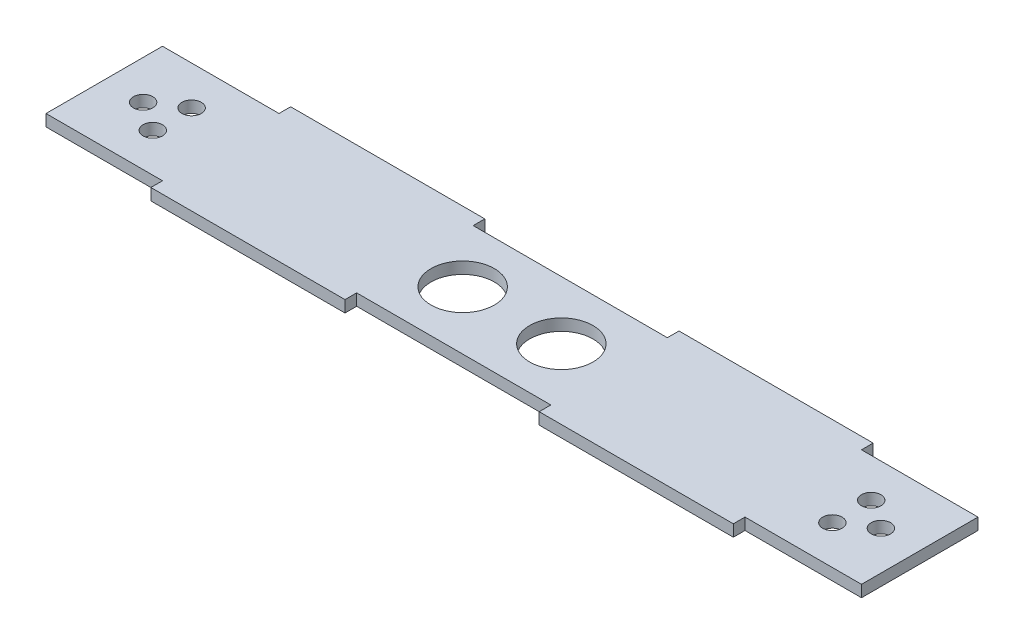
SolidWorks part; units mm, degrees
other "Markup1"
sketch "Sketch5" plane through (-105, 3, 18) normal (0, 1, 0.0048) x (1, 0, 0)
material "3mm Birch Ply Wood"
ref_plane "Front Plane" through (0, 0, 0) normal (0, 0, 1) x (1, 0, 0)
ref_plane "Top Plane" through (0, 0, 0) normal (0, 1, 0) x (1, 0, 0)
ref_plane "Right Plane" through (0, 0, 0) normal (1, 0, 0) x (0, 0, -1)
sketch "Sketch1" plane through (0, 0, 0) normal (0, 1, 0) x (1, 0, 0)
  line L1 (-105, -15) -> (105, -15)
  line L2 (-105, -15) -> (-105, 15)
  line L3 (-105, 15) -> (105, 15)
  line L4 (105, -15) -> (105, 15)
  line L5 (-105, -15) -> (105, 15) construction
  line L6 (-105, 15) -> (105, -15) construction
  point P0 (0, 0)
extrude "Boss-Extrude1" add sketch "Sketch1" along normal blind 3
sketch "Sketch2" plane through (0, 0, 0) normal (0, 1, 0) x (1, 0, 0)
  line L0 (-105, 0) -> (105, 0) construction
  line L1 (-105, 15) -> (-105, -15) construction
  line L2 (105, -15) -> (105, 15) construction
  line L3 (-105, 15) -> (-75, 15) construction
  line L4 (105, 15) -> (-105, 15) construction
  line L5 (-75, 15) -> (-75, 18)
  line L6 (-75, 18) -> (-25, 18)
  line L7 (-75, 15) -> (-25, 15)
  line L8 (-25, 15) -> (-25, 18)
  line L9 (-25, 18) -> (25, 18) construction
  line L10 (25, 18) -> (25, 15)
  line L11 (25, 15) -> (75, 15)
  line L12 (25, 18) -> (75, 18)
  line L13 (75, 18) -> (75, 15)
  line L14 (-25, -18) -> (25, -18) construction
  line L15 (-105, -15) -> (-75, -15) construction
  line L16 (75, -18) -> (75, -15)
  line L17 (25, -18) -> (75, -18)
  line L18 (25, -15) -> (75, -15)
  line L19 (25, -18) -> (25, -15)
  line L20 (-25, -15) -> (-25, -18)
  line L21 (-75, -15) -> (-25, -15)
  line L22 (-75, -18) -> (-25, -18)
  line L23 (-75, -15) -> (-75, -18)
extrude "Boss-Extrude2" add sketch "Sketch2" along normal blind 3
sketch "Sketch3" plane through (0, 3, 0) normal (0, 1, 0) x (1, 0, 0)
  line L0 (0, 15) -> (0, 0) construction
  line L1 (25, 15) -> (-25, 15) construction
  line L2 (0, 0) -> (-12.7, 0) construction
  circle A0 centre (-12.7, 0) radius 8.15
  circle A1 centre (12.7, 0) radius 8.15
extrude "Cut-Extrude1" cut sketch "Sketch3" against normal blind 10
sketch "Sketch4" plane through (0, 3, 0) normal (0, 1, 0) x (1, 0, 0)
  line L0 (-105, 0) -> (-95, 0) construction
  line L1 (-105, 15) -> (-105, -15) construction
  line L2 (-95, 0) -> (-87.5, 0) construction
  line L3 (-87.5, -5) -> (-87.5, 5) construction
  line L4 (0, 15) -> (0, -15) construction
  line L5 (25, 15) -> (-25, 15) construction
  line L6 (-25, -15) -> (25, -15) construction
  line L7 (87.5, -5) -> (87.5, 5) construction
  line L8 (95, 0) -> (87.5, 0) construction
  line L9 (105, 0) -> (95, 0) construction
  circle A0 centre (-95, 0) radius 2.5
  circle A1 centre (-87.5, 5) radius 2.5
  circle A2 centre (-87.5, -5) radius 2.5
  circle A3 centre (87.5, -5) radius 2.5
  circle A4 centre (87.5, 5) radius 2.5
  circle A5 centre (95, 0) radius 2.5
  point P10 (-87.5, 0)
  point P26 (87.5, 0)
extrude "Cut-Extrude2" cut sketch "Sketch4" against normal blind 10
